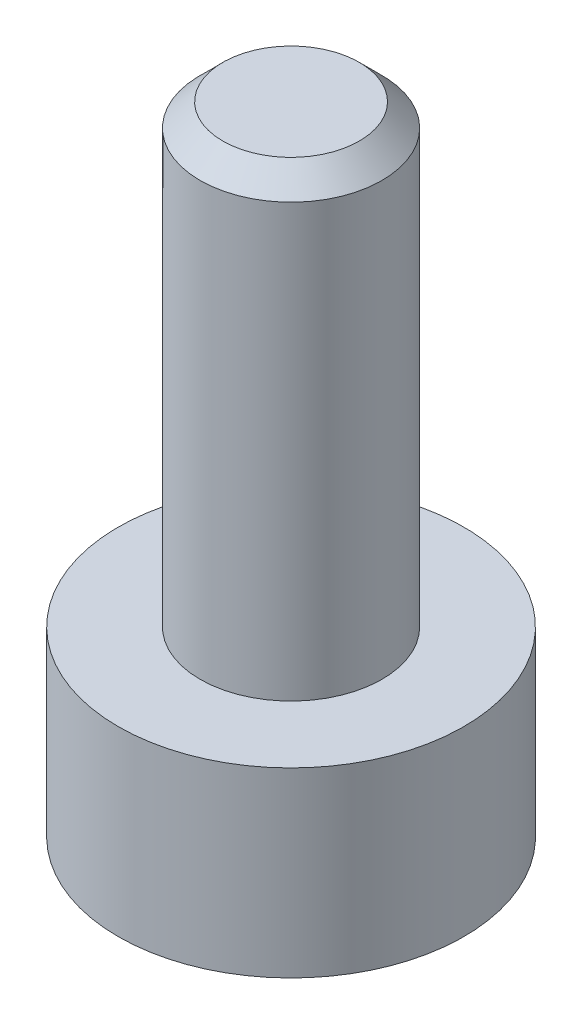
SolidWorks part; units mm, degrees
material "Stainless Steel (ferritic)"
ref_plane "Front Plane" through (0, 0, 0) normal (0, 0, 1) x (1, 0, 0)
ref_plane "Top Plane" through (0, 0, 0) normal (0, 1, 0) x (1, 0, 0)
ref_plane "Right Plane" through (0, 0, 0) normal (1, 0, 0) x (0, 0, -1)
sketch "Sketch1" plane through (0, 0, 0) normal (0, 1, 0) x (1, 0, 0)
  circle A0 centre (0, 0) radius 1.9
  dimension "D1" = 3.8
extrude "Boss-Extrude1" add sketch "Sketch1" along normal blind 2
sketch "Sketch2" plane through (0, 2, 0) normal (0, 1, 0) x (1, 0, 0)
  circle A0 centre (0, 0) radius 1
extrude "Boss-Extrude2" add sketch "Sketch2" along normal blind 5
sketch "Sketch3" plane through (0, 0, 0) normal (0, -1, 0) x (1, 0, 0)
  line L1 (0, -0.8426) -> (0.75, -0.4096)
  line L2 (0.75, -0.4096) -> (0.75, 0.4564)
  line L3 (0.75, 0.4564) -> (0, 0.8894)
  line L4 (0, 0.8894) -> (-0.75, 0.4564)
  line L5 (-0.75, 0.4564) -> (-0.75, -0.4096)
  line L6 (-0.75, -0.4096) -> (0, -0.8426)
  circle A0 centre (0, 0.0234) radius 0.75 construction
  dimension "D1" = 1.5
extrude "Cut-Extrude1" cut sketch "Sketch3" against normal blind 1
chamfer "Chamfer1" distance 0.25 angle 45 1 edges at (0, 7, 1)
cosmetic thread "Cosmetic Thread1" parameters "D2"=1.548
